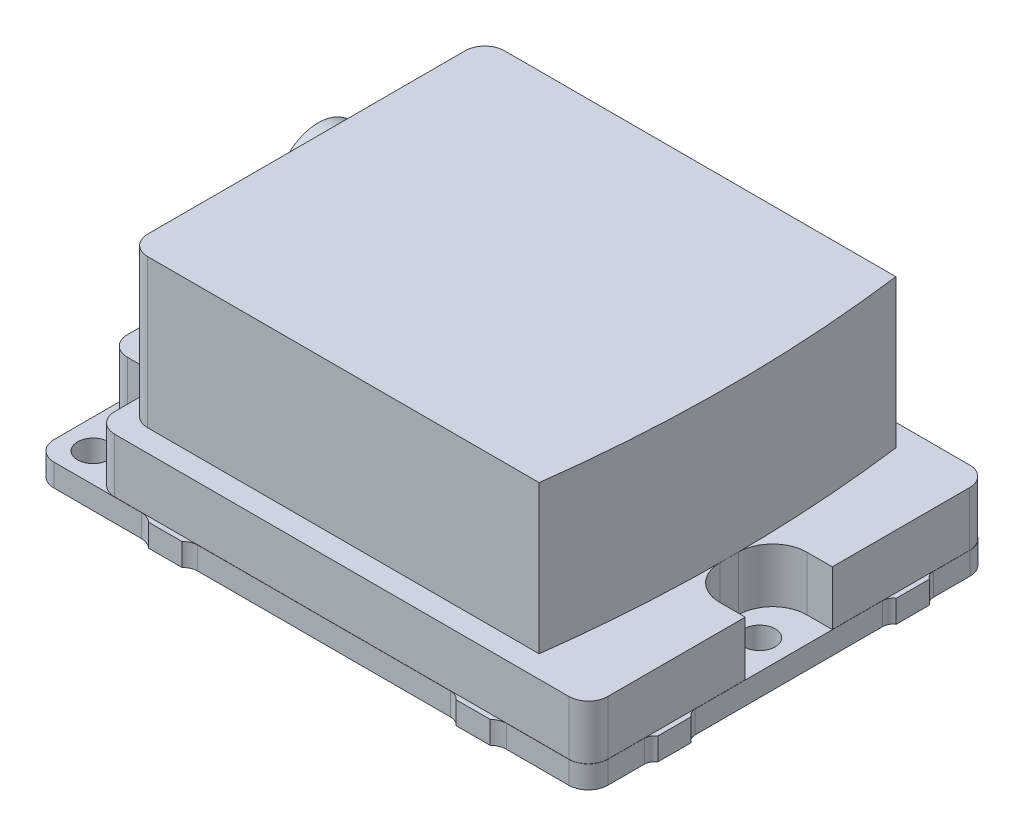
SolidWorks part; units mm, degrees
ref_plane "Front Plane" through (0, 0, 0) normal (0, 0, 1) x (1, 0, 0)
ref_plane "Top Plane" through (0, 0, 0) normal (0, 1, 0) x (1, 0, 0)
ref_plane "Right Plane" through (0, 0, 0) normal (1, 0, 0) x (0, 0, -1)
sketch "Sketch1" plane through (0, 0, 0) normal (0, 1, 0) x (1, 0, 0)
  line L1 (-28.3, -20.5) -> (28.3, -20.5)
  line L2 (-28.3, -20.5) -> (-28.3, 20.5)
  line L3 (-28.3, 20.5) -> (28.3, 20.5)
  line L4 (28.3, -20.5) -> (28.3, 20.5)
  line L5 (-28.3, -20.5) -> (28.3, 20.5) construction
  line L6 (-28.3, 20.5) -> (28.3, -20.5) construction
  point P0 (0, 0)
extrude "Boss-Extrude1" add sketch "Sketch1" along normal blind 2.3
sketch "Sketch2" plane through (0, 2.3, 0) normal (0, 1, 0) x (1, 0, 0)
  line L0 (0, 0) -> (0, 12.239) construction
  line L1 (28.285, -20.48) -> (-28.285, -20.48)
  line L2 (28.285, -20.48) -> (28.285, 20.48)
  line L3 (28.285, 20.48) -> (-28.285, 20.48)
  line L4 (-28.285, -20.48) -> (-28.285, 20.48)
  line L5 (28.285, -20.48) -> (-28.285, 20.48) construction
  line L6 (28.285, 20.48) -> (-28.285, -20.48) construction
  line L7 (0, 0) -> (13.1918, 0) construction
  line L8 (22.185, 0) -> (28.285, 0) construction
  line L9 (-28.285, 13.02) -> (-22.125, 13.02)
  line L10 (-22.125, 13.02) -> (-22.125, 20.48)
  line L11 (28.285, 4.45) -> (22.185, 4.45)
  line L12 (28.285, 4.45) -> (28.285, -4.45)
  line L13 (28.285, -4.45) -> (22.185, -4.45)
  line L14 (-28.285, -13.02) -> (-22.125, -13.02)
  line L15 (-22.125, -13.02) -> (-22.125, -20.48)
  line L16 (22.185, 4.45) -> (22.185, -4.45)
  line L17 (-28.285, 13.02) -> (-28.285, 20.48)
  line L18 (-28.285, -13.02) -> (-28.285, -20.48)
  point P0 (0, 0)
extrude "Boss-Extrude2" add sketch "Sketch2" along normal blind 5.55 contours L16 L11 L2 L3 L10 L9 L4 L14 L15 L1 L13
sketch "Sketch3" plane through (0, 7.85, 0) normal (0, 1, 0) x (1, 0, 0)
  line L1 (-19, -18.225) -> (21, -18.225)
  line L2 (-21, -16.225) -> (-21, 16.225)
  line L3 (-19, 18.225) -> (21, 18.225)
  line L5 (-21, -18.225) -> (21, 18.225) construction
  line L6 (-21, 18.225) -> (21, -18.225) construction
  arc A0 (21, -18.225) -> (21, 18.225) centre (-118.5554, 0) ccw
  arc A1 (-21, 16.225) -> (-19, 18.225) centre (-19, 16.225) cw
  arc A2 (-21, -16.225) -> (-19, -18.225) centre (-19, -16.225) ccw
  point P0 (0, 0)
  dimension "D1" = 2
extrude "Boss-Extrude3" add sketch "Sketch3" along normal blind 15.15
fillet "Fillet1" radius 2 12 edges at (-22.125, 5.075, -13.02) (-28.285, 5.075, -13.02) (-22.125, 5.075, -20.48) (-28.285, 5.075, 13.02) (-22.125, 5.075, 13.02) (-22.125, 5.075, 20.48) (28.3, 1.15, 20.5) (28.285, 5.075, 20.48) (28.3, 1.15, -20.5) (28.285, 5.075, -20.48) (-28.3, 1.15, 20.5) (-28.3, 1.15, -20.5)
sketch "Sketch4" plane through (0, 0, 0) normal (0, 1, 0) x (1, 0, 0)
  line L0 (28.785, 12.18) -> (29.8277, 12.18) construction
  line L1 (28.285, 4.45) -> (28.285, 18.48) construction
  line L4 (28.285, 13.88) -> (28.285, 10.48)
  line L6 (28.785, 13.88) -> (28.785, 10.48)
  line L7 (28.3, -18.5) -> (28.3, 18.5) construction
  line L8 (28.3, 14.7724) -> (28.3, 9.5876)
  line L9 (28.3, 0) -> (32.8587, 0) construction
  line L10 (28.785, -13.88) -> (28.785, -10.48)
  line L11 (28.3, -14.7724) -> (28.3, -9.5876)
  arc A0 (28.3, 14.7724) -> (28.785, 13.88) centre (29.3634, 14.7724) ccw
  arc A1 (28.3, 9.5876) -> (28.785, 10.48) centre (29.3634, 9.5876) cw
  arc A2 (28.3, -14.7724) -> (28.785, -13.88) centre (29.3634, -14.7724) cw
  arc A3 (28.3, -9.5876) -> (28.785, -10.48) centre (29.3634, -9.5876) ccw
  dimension "D2" = 3.4
extrude "Boss-Extrude5" add sketch "Sketch4" along direction (0, -1, 0) on the side of the normal up to surface (2.3 mm away) contours L8 A1 L6 A0 | A3 L11 A2 L10
sketch "Sketch5" plane through (29.4347, 0, -17.005) normal (0, 1, 0) x (0, 0, -1)
  line L2 (-37.505, 43.871) -> (-37.99, 43.871) construction
  line L3 (3.495, 3.1347) -> (3.495, 55.7347) construction
  line L4 (3.495, 9.6293) -> (3.495, 9.4863)
  line L5 (-37.505, 12.4285) -> (-37.99, 12.4285) construction
  line L6 (3.98, 14.1497) -> (3.98, 10.7072)
  line L8 (3.495, 15.2277) -> (3.495, 9.6293)
  line L9 (-12.555, 1.1497) -> (1.475, 1.1497) construction
  line L10 (3.495, 12.4285) -> (3.98, 12.4285) construction
  line L11 (-37.505, 46.8132) -> (-37.505, 46.6702)
  line L12 (3.495, 43.871) -> (3.98, 43.871) construction
  line L13 (3.495, 41.0718) -> (3.495, 46.6702)
  line L14 (3.98, 42.1497) -> (3.98, 45.5922)
  line L15 (-17.005, 57.7197) -> (-17.005, 64.4158) construction
  line L16 (-28.025, 57.7197) -> (-5.985, 57.7197) construction
  line L17 (3.495, 46.8132) -> (3.495, 46.6702)
  line L18 (-37.99, 42.1497) -> (-37.99, 45.5922)
  line L19 (-37.505, 41.0718) -> (-37.505, 46.6702)
  line L20 (-37.505, 15.2277) -> (-37.505, 9.6293)
  line L21 (-37.99, 14.1497) -> (-37.99, 10.7072)
  line L22 (-37.505, 9.6293) -> (-37.505, 9.4863)
  arc A2 (3.495, 15.2277) -> (3.98, 14.1497) centre (4.9354, 15.2277) ccw
  arc A3 (3.98, 10.7072) -> (3.495, 9.4863) centre (5.2744, 9.4863) ccw
  arc A4 (3.98, 45.5922) -> (3.495, 46.8132) centre (5.2744, 46.8132) cw
  arc A5 (3.495, 41.0718) -> (3.98, 42.1497) centre (4.9354, 41.0718) cw
  arc A6 (-37.505, 41.0718) -> (-37.99, 42.1497) centre (-38.9454, 41.0718) ccw
  arc A7 (-37.99, 45.5922) -> (-37.505, 46.8132) centre (-39.2844, 46.8132) ccw
  arc A8 (-37.99, 10.7072) -> (-37.505, 9.4863) centre (-39.2844, 9.4863) cw
  arc A9 (-37.505, 15.2277) -> (-37.99, 14.1497) centre (-38.9454, 15.2277) cw
  dimension "D4" = 0.485
  dimension "D2" = 13
  dimension "D5" = 0.485
extrude "Boss-Extrude6" add sketch "Sketch5" along normal up to surface (2.3 mm away) up to face at (-3.803, 2.3, 0)
sketch "Sketch6" plane through (0, 2.3, 0) normal (0, 1, 0) x (1, 0, 0)
  line L0 (-17.3785, 20.5) -> (-26.3, 20.5) construction
  line L1 (-28.3, 18.5) -> (-28.3, -18.5) construction
  line L2 (-28.3, 0) -> (-40.154, 0) construction
  line L3 (28.3, -9.5876) -> (28.3, 9.5876) construction
  line L4 (-21, 0) -> (36.0528, 0) construction
  line L5 (-21, 16.225) -> (-21, -16.225) construction
  circle A0 centre (-25.3, 17.5) radius 1.6
  circle A1 centre (-25.3, -17.5) radius 1.6
  circle A2 centre (25.3, 0) radius 1.6
  dimension "D1" = 3
  dimension "D3" = 3
  dimension "D2" = 3
extrude "Cut-Extrude1" cut sketch "Sketch6" against normal through all
fillet "Fillet2" radius 3.5 2 edges at (22.185, 5.075, 4.45) (22.185, 5.075, -4.45)
sketch "Sketch7" plane through (-21, 0, 0) normal (-1, 0, 0) x (0, 0, 1)
  line L0 (18.225, 23) -> (18.225, 7.85) construction
  line L1 (-16.225, 23) -> (16.225, 23) construction
  line L2 (-0.5282, 14.265) -> (-0.5282, 17.2665) construction
  line L3 (2.3518, 14.265) -> (2.3518, 17.2665) construction
  line L4 (-6.66, 20.3968) -> (7.06, 20.3968) construction
  circle A0 centre (7.06, 14.265) radius 4.7082
  circle A1 centre (-6.66, 14.265) radius 6.1318 construction
  dimension "D1" = 11.165
  dimension "D2" = 8.735
  dimension "D3" = 2.88
  dimension "D4" = 9.4163
extrude "Boss-Extrude7" add sketch "Sketch7" along normal blind 0.2 contours A0
ref_plane "Plane1" through (0, 0, -6.66) normal (0, 0, -1) x (-1, 0, 0)
sketch "Sketch9" plane through (0, 0, -6.66) normal (0, 0, -1) x (-1, 0, 0)
  line L0 (21, 14.265) -> (24, 14.265) construction
  line L1 (21, 9.5568) -> (21, 18.9732) construction
  line L2 (21, 20.3968) -> (22.15, 20.3968) construction
  line L3 (21, 8.1332) -> (21, 20.3968) construction
  line L4 (21, 23) -> (21, 7.85) construction
  line L5 (21.6362, 18.665) -> (24.6021, 18.665) construction
  line L6 (24, 14.265) -> (24, 18.665) construction
  line L7 (24, 18.665) -> (22.15, 20.3968) construction
  line L8 (21, 20.3968) -> (21, 14.265)
  line L9 (21, 14.265) -> (24, 14.265)
  line L10 (24, 14.265) -> (24, 18.665)
  line L11 (24, 18.665) -> (22.15, 20.3968)
  line L12 (22.15, 20.3968) -> (21, 20.3968)
  dimension "D1" = 4.4
revolve "Revolve1" add sketch "Sketch9" angle 360 about L9
sketch "Sketch11" plane through (-24, 0, 0) normal (-1, 0, 0) x (0, 0, 1)
  circle A0 centre (-6.66, 14.265) radius 4.425
extrude "Boss-Extrude8" add sketch "Sketch11" along normal blind 2.45
sketch "Sketch12" plane through (-26.45, 0, 0) normal (-1, 0, 0) x (0, 0, 1)
  circle A0 centre (-6.66, 14.265) radius 3.925
  circle A1 centre (-6.66, 14.265) radius 4.425 construction
  dimension "D1" = 0.5
extrude "Cut-Extrude2" cut sketch "Sketch12" against normal blind 2.45 and the other way blind 10
sketch "Sketch13" plane through (-21.2, 0, 0) normal (-1, 0, 0) x (0, 0, 1)
  line L0 (7.06, 18.9732) -> (7.06, 9.5568) construction
  line L2 (2.3518, 14.265) -> (4.7059, 10.1876)
  line L3 (4.7059, 10.1876) -> (9.4141, 10.1876)
  line L4 (9.4141, 10.1876) -> (11.7682, 14.265)
  line L5 (11.7682, 14.265) -> (9.4141, 18.3424)
  line L6 (9.4141, 18.3424) -> (4.7059, 18.3424)
  line L7 (4.7059, 18.3424) -> (2.3518, 14.265)
  circle A0 centre (7.06, 14.265) radius 4.7082 construction
  circle A1 centre (7.06, 14.265) radius 4.7082 construction
  circle A2 centre (7.06, 14.265) radius 4.0774 construction
extrude "Boss-Extrude10" add sketch "Sketch13" along normal blind 1
